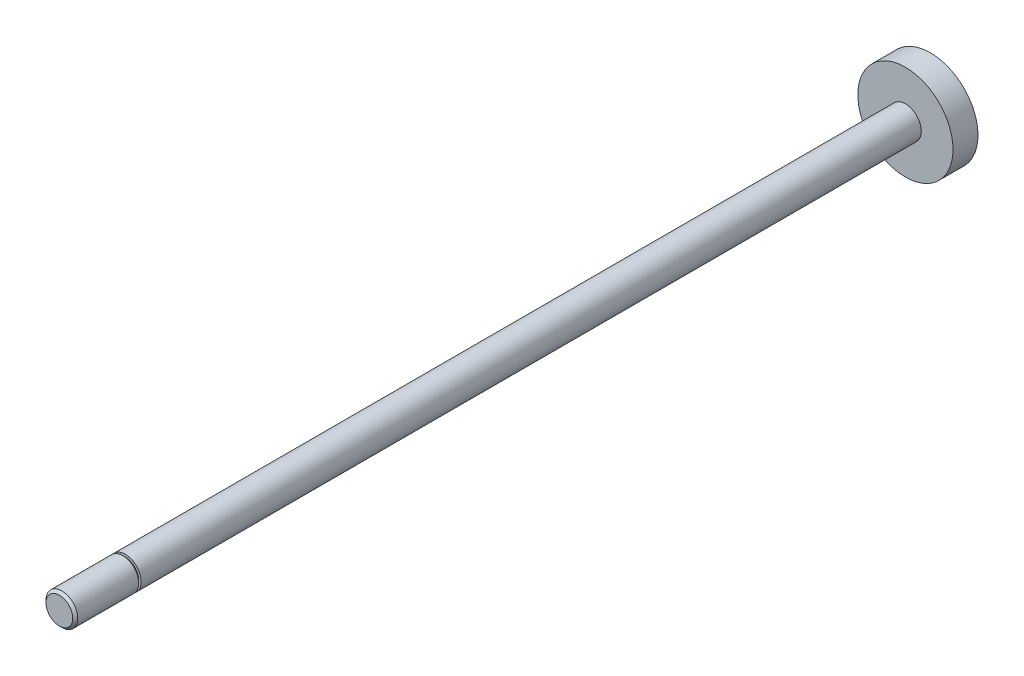
SolidWorks part; units mm, degrees
material "AISI 316 Annealed Stainless Steel Bar (SS)"
ref_plane "Front" through (0, 0, 0) normal (0, 0, 1) x (1, 0, 0)
ref_plane "Top" through (0, 0, 0) normal (0, 1, 0) x (1, 0, 0)
ref_plane "Right" through (0, 0, 0) normal (1, 0, 0) x (0, 0, -1)
sketch "Sketch1" plane through (0, 0, 0) normal (0, 0, 1) x (1, 0, 0)
  circle A0 centre (0, 0) radius 3.175
  dimension "MM" = 6.35
extrude "Extrude1" add sketch "Sketch1" along normal up to surface (171.831 mm away)
sketch "Sketch2" plane through (0, 0, 0) normal (0, 0, 1) x (1, 0, 0)
  circle A0 centre (0, 0) radius 9.525
  dimension "Bore" = 19.05
extrude "Piston" add sketch "Sketch2" along normal mid plane 5
sketch "Sketch3" plane through (0, 0, 0) normal (1, 0, 0) x (0, 0, -1)
  line L0 (-171.831, 9.525) -> (-158.631, 9.525)
  line L1 (-171.831, 9.525) -> (-171.831, 2.675)
  line L2 (-171.831, 2.675) -> (-171.331, 3.175)
  line L3 (-171.331, 3.175) -> (-159.131, 3.175)
  line L4 (-159.131, 3.175) -> (-159.131, 2.675)
  line L5 (-159.131, 2.675) -> (-158.631, 2.675)
  line L6 (-158.631, 2.675) -> (-158.631, 9.525)
  line L8 (-171.831, 3.175) -> (-171.831, -3.175) construction
  line L9 (2.5, 9.525) -> (-2.5, 9.525) construction
  line L10 (0, 0) -> (-105.1844, 0) construction
  dimension "D1" = 45
  dimension "KK" = 6.35
  dimension "D2" = 0.5
  dimension "D3" = 0.5
  dimension "D4" = 0.5
  dimension "A" = 12.7
revolve "Threads" cut sketch "Sketch3" angle 360 about L10
sketch "Sketch4" [suppressed] plane through (0, 0, 0) normal (0, 1, 0) x (1, 0, 0)
  line L0 (0, 0) -> (0, -104.7006) construction
  line L1 (7.9375, -146.177) -> (6.35, -146.177)
  line L2 (7.9375, -146.177) -> (-7.9375, -146.177) construction
  line L3 (6.35, -146.177) -> (6.35, -136.575)
  line L4 (6.35, -136.575) -> (7.9375, -134.9875)
  line L5 (7.9375, -134.9875) -> (7.9375, -146.177)
  line L6 (7.9375, -142.875) -> (7.9375, -2.5) construction
  line L7 (-7.9375, -134.9875) -> (-7.9375, -146.177)
  line L8 (-6.35, -136.575) -> (-7.9375, -134.9875)
  line L9 (-6.35, -146.177) -> (-6.35, -136.575)
  line L10 (-7.9375, -146.177) -> (-6.35, -146.177)
  dimension "D" = 6.35
  dimension "K" = 3.048
extrude "Flats" [suppressed] cut sketch "Sketch4" against normal through all and the other way through all
